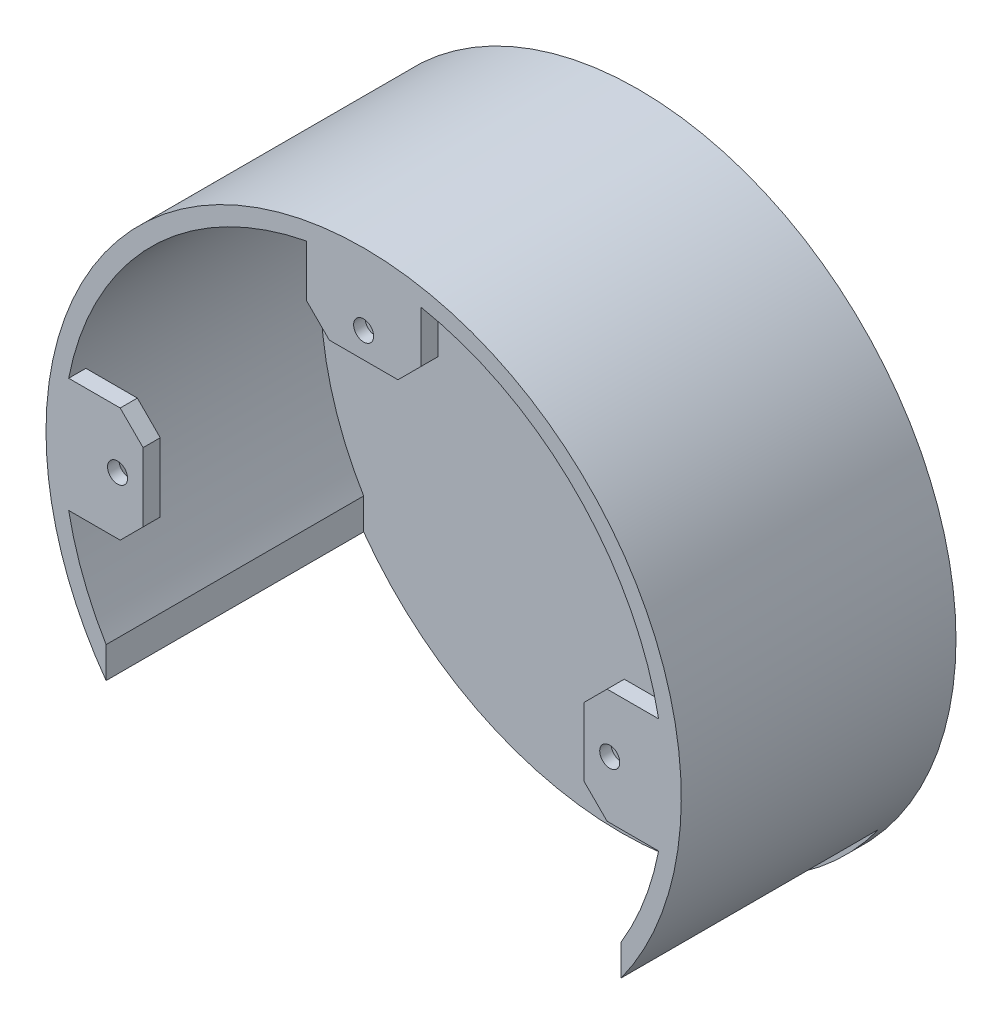
SolidWorks part; units mm, degrees
ref_plane "Front Plane" through (0, 0, 0) normal (0, 0, 1) x (1, 0, 0)
ref_plane "Top Plane" through (0, 0, 0) normal (0, 1, 0) x (1, 0, 0)
ref_plane "Right Plane" through (0, 0, 0) normal (1, 0, 0) x (0, 0, -1)
sketch "Sketch1" plane through (0, 0, 0) normal (0, 0, 1) x (1, 0, 0)
  circle A0 centre (0, 0) radius 52.5
  circle A1 centre (0, 0) radius 55.5
  dimension "D1" = 105
  dimension "D2" = 3
extrude "Boss-Extrude1" add sketch "Sketch1" along normal blind 45
sketch "Sketch2" plane through (0, 0, 0) normal (0, 0, -1) x (-1, 0, 0)
  line L0 (-10.45, 0) -> (10.45, 0) construction
  line L1 (0, 10.45) -> (0, -10.45) construction
  circle A0 centre (0, 0) radius 55.5 construction
  circle A1 centre (0, 0) radius 55.5
  circle A2 centre (0, 0) radius 5.1
  circle A3 centre (-10.45, 0) radius 1.7
  circle A4 centre (10.45, 0) radius 1.7
  circle A5 centre (0, 10.45) radius 1.7
  circle A6 centre (0, -10.45) radius 1.7
  point P9 (0, 0)
  point P12 (0, 0)
  dimension "D1" = 10.2
  dimension "D3" = 3.4
  dimension "D2" = 20.9
  dimension "D4" = 20.9
extrude "Boss-Extrude2" add sketch "Sketch2" along normal blind 3
sketch "Sketch3" plane through (0, 0, 0) normal (0, 1, 0) x (1, 0, 0)
  line L1 (-45, 0) -> (45, 0)
  line L2 (-45, 0) -> (-45, -75.0464)
  line L3 (-45, -75.0464) -> (45, -75.0464)
  line L4 (45, 0) -> (45, -75.0464)
  point P4 (0, 0)
  dimension "D1" = 90
extrude "Cut-Extrude1" cut sketch "Sketch3" against normal through all
sketch "Sketch4" plane through (0, 0, 45) normal (0, 0, 1) x (1, 0, 0)
  line L0 (51.5388, -10) -> (38.5388, -10)
  line L1 (38.5388, -10) -> (38.5388, 10)
  line L2 (38.5388, 10) -> (51.5388, 10)
  line L3 (43, 0) -> (-43, 0) construction
  line L7 (-51.5388, 10) -> (-38.5388, 10)
  line L8 (-38.5388, 10) -> (-38.5388, -10)
  line L9 (-38.5388, -10) -> (-51.5388, -10)
  line L10 (10, 51.5388) -> (10, 38.5388)
  line L11 (10, 38.5388) -> (-10, 38.5388)
  line L12 (-10, 38.5388) -> (-10, 51.5388)
  line L13 (-10, -51.5388) -> (-10, -38.5388) [skipped]
  line L14 (-10, -38.5388) -> (10, -38.5388) [skipped]
  line L15 (10, -38.5388) -> (10, -51.5388) [skipped]
  arc A0 (45, -27.0416) -> (-45, -27.0416) centre (0, 0) ccw construction
  arc A1 (51.5388, 10) -> (51.5388, -10) centre (0, 0) cw
  circle A2 centre (43, 0) radius 1.75
  circle A3 centre (-43, 0) radius 1.75
  circle A4 centre (0, 43) radius 1.75
  arc A6 (-51.5388, -10) -> (-51.5388, 10) centre (0, 0) cw
  arc A7 (-10, 51.5388) -> (10, 51.5388) centre (0, 0) cw
  arc A8 (10, -51.5388) -> (-10, -51.5388) centre (0, 0) cw [skipped]
  point P17 (38.5388, 0)
  point P19 (0, 0)
  dimension "D1" = 3.5
  dimension "D2" = 86
  dimension "D3" = 43
  dimension "D4" = 20
  dimension "D5" = 13
  dimension "D6" = 4
extrude "Boss-Extrude3" add sketch "Sketch4" against normal blind 3
chamfer "Chamfer1" distance 4 angle 45 6 edges at (-38.5388, 10, 43.5) (-38.5388, -10, 43.5) (10, 38.5388, 43.5) (-10, 38.5388, 43.5) (38.5388, -10, 43.5) (38.5388, 10, 43.5)
sketch "Sketch6" plane through (0, 0, -3) normal (0, 0, -1) x (-1, 0, 0)
  line L0 (-35, -37) -> (35, -37) construction
  line L1 (-22, -13) -> (22, -13) construction
  circle A0 centre (0, 0) radius 20 construction
  circle A1 centre (0, 0) radius 55 construction
  circle A3 centre (-22, -13) radius 3
  circle A4 centre (22, -13) radius 3
  circle A5 centre (-35, -37) radius 3
  circle A6 centre (35, -37) radius 3
  point P12 (0, -13)
  point P13 (0, -37)
  dimension "D1" = 40
  dimension "D2" = 110
  dimension "D3" = 6
  dimension "42" = 44
  dimension "D5" = 70
  dimension "D6" = 24
  dimension "D7" = 37
extrude "Boss-Extrude4" [suppressed] add sketch "Sketch6" along normal blind 20
sketch "Sketch7" [suppressed] plane through (0, 0, -23) normal (0, 0, -1) x (-1, 0, 0)
  line L0 (-19.0788, -6) -> (-49.4874, -24)
  line L1 (19.0788, -6) -> (49.4874, -24)
  circle A0 centre (0, 0) radius 55 construction
  circle A1 centre (0, 0) radius 55 construction
  circle A2 centre (0, 0) radius 20 construction
  circle A3 centre (0, 0) radius 20 construction
  arc A4 (19.0788, -6) -> (-19.0788, -6) centre (0, 0) cw
  arc A5 (49.4874, -24) -> (-49.4874, -24) centre (0, 0) cw
  circle M1 centre (-35, -37) radius 3
  dimension "D1" = 6
  dimension "D2" = 24
extrude "Boss-Extrude5" [suppressed] add sketch "Sketch7" along normal blind 2 contours A5 L1 A4 L0 M1 | M1
sketch "Sketch8" plane through (0, 0, -3) normal (0, 0, -1) x (-1, 0, 0)
  line L0 (0, 0) -> (57.6058, -57.6058) construction
  line L1 (0, 0) -> (-25.244, 0) construction
  line L2 (0, 0) -> (-54.7312, -54.7312) construction
  line L3 (0, 0) -> (0, -48) construction
  circle A0 centre (16.9706, -16.9706) radius 1.7 construction
  circle A1 centre (34.6482, -34.6482) radius 1.7 construction
  circle A2 centre (-16.9706, -16.9706) radius 1.7 construction
  circle A3 centre (-34.6482, -34.6482) radius 1.7 construction
  circle A9 centre (34.6482, 34.6482) radius 1.7
  circle A10 centre (16.9706, 16.9706) radius 1.7
  circle A11 centre (-16.9706, 16.9706) radius 1.7
  circle A12 centre (-34.6482, 34.6482) radius 1.7
  circle A13 centre (0, -48) radius 1.7
  circle A14 centre (-48, 0) radius 1.7
  circle A15 centre (0, 48) radius 1.7
  circle A16 centre (48, 0) radius 1.7
  dimension "D1" = 3.4
  dimension "D7" = 48
  dimension "D2" = 135
  dimension "D3" = 25
  dimension "D4" = 24
  dimension "D5" = 24
  dimension "D6" = 25
  dimension "D8" = 4
  dimension "D9" = 48
extrude "Cut-Extrude2" cut sketch "Sketch8" against normal blind 10
sketch "Sketch9" plane through (0, 0, 42) normal (0, 0, -1) x (-1, 0, 0)
  circle A0 centre (-43, 0) radius 3.25
  circle A1 centre (0, 43) radius 3.25
  circle A2 centre (43, 0) radius 3.25
  dimension "D1" = 6.5
extrude "Cut-Extrude3" cut sketch "Sketch9" against normal blind 1
sketch "Sketch10" plane through (0, 0, -3) normal (0, 0, -1) x (-1, 0, 0)
  line L0 (0, 0) -> (63.3925, 0) construction
  line L1 (51.9547, 6) -> (48.9745, 5.6558)
  line L2 (48.9745, -5.6558) -> (51.9547, -6)
  line L3 (6, -51.9547) -> (5.6558, -48.9745)
  line L4 (-5.6558, -48.9745) -> (-6, -51.9547)
  line L5 (-51.9547, -6) -> (-48.9745, -5.6558)
  line L6 (-48.9745, 5.6558) -> (-51.9547, 6)
  line L7 (-6, 51.9547) -> (-5.6558, 48.9745)
  line L8 (5.6558, 48.9745) -> (6, 51.9547)
  arc A0 (51.9547, 6) -> (51.9547, -6) centre (0, 0) cw
  arc A1 (6, -51.9547) -> (-6, -51.9547) centre (0, 0) cw
  circle A2 centre (0, 0) radius 55.5 construction
  arc A3 (48.9745, 5.6558) -> (48.9745, -5.6558) centre (0, 0) cw
  arc A4 (5.6558, -48.9745) -> (-5.6558, -48.9745) centre (0, 0) cw
  arc A5 (-51.9547, -6) -> (-51.9547, 6) centre (0, 0) cw
  arc A6 (-48.9745, -5.6558) -> (-48.9745, 5.6558) centre (0, 0) cw
  arc A7 (-6, 51.9547) -> (6, 51.9547) centre (0, 0) cw
  arc A8 (-5.6558, 48.9745) -> (5.6558, 48.9745) centre (0, 0) cw
  point P6 (52.3, 0)
  dimension "D1" = 3.2
  dimension "D2" = 12
  dimension "D3" = 3
  dimension "D4" = 4
extrude "Boss-Extrude6" [suppressed] add sketch "Sketch10" along normal blind 10
fillet "Fillet1" [suppressed] radius 1.5
